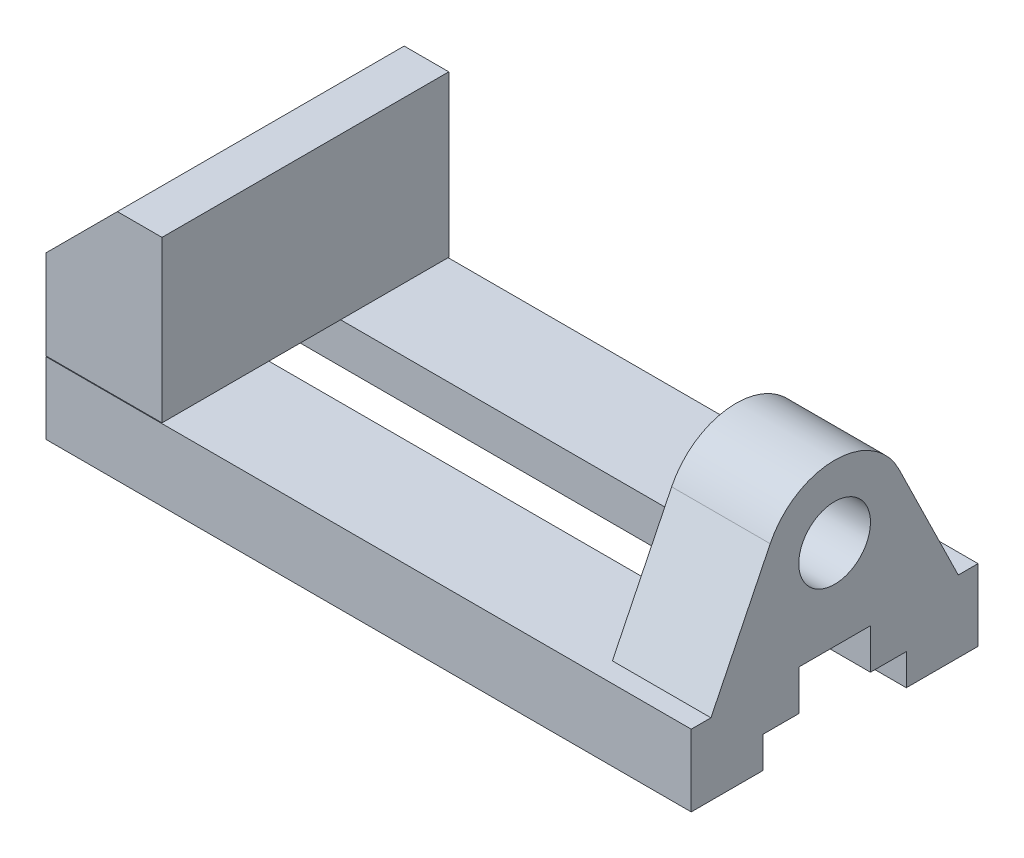
SolidWorks part; units mm, degrees
ref_plane "Front Plane" through (0, 0, 0) normal (0, 0, 1) x (1, 0, 0)
ref_plane "Top Plane" through (0, 0, 0) normal (0, 1, 0) x (1, 0, 0)
ref_plane "Right Plane" through (0, 0, 0) normal (1, 0, 0) x (0, 0, -1)
sketch "Sketch1" plane through (0, 0, 0) normal (0, 0, 1) x (1, 0, 0)
  line L1 (72, 8) -> (-72, 8)
  line L2 (72, 8) -> (72, -8)
  line L3 (72, -8) -> (-72, -8)
  line L4 (-72, 8) -> (-72, -8)
  line L5 (72, 8) -> (-72, -8) construction
  line L6 (72, -8) -> (-72, 8) construction
  point P0 (0, 0)
  dimension "D1" = 16
  dimension "D2" = 144
extrude "Boss-Extrude1" add sketch "Sketch1" along normal mid plane 64
ref_plane "Plane1" through (0, 0, 32) normal (0, 0, 1) x (1, 0, 0)
sketch "Sketch2" plane through (0, 0, 32) normal (0, 0, 1) x (1, 0, 0)
  line L0 (-72, 8.15) -> (-46.1084, 8.15)
  line L1 (-72, -8) -> (72, -8) construction
  line L6 (-56.0667, 44) -> (-72, 28.0667)
  line L8 (-72, 8.15) -> (-72, 28.0667)
  line L9 (-56.0667, 44) -> (-46.1084, 44)
  line L10 (-46.1084, 8.15) -> (-46.1084, 44)
  point P1 (0, 0)
  point P2 (0, 0)
  point P3 (-71.3163, 28.7504)
  dimension "D1" = 9.9583
  dimension "D2" = 35.85
  dimension "D3" = 22.5331
  dimension "D4" = 46.1084
  dimension "D5" = 72
  dimension "D6" = 15.9333
  dimension "D7" = 16.15
  dimension "D8" = 44
  dimension "D9" = 45
extrude "Boss-Extrude2" add sketch "Sketch2" against normal blind 64
ref_plane "Plane2" through (72, 0, 0) normal (1, 0, 0) x (0, 0, -1)
sketch "Sketch3" plane through (72, 0, 0) normal (1, 0, 0) x (0, 0, -1)
  line L0 (-27.5969, 8) -> (-32, 8)
  line L1 (-32, -8) -> (32, -8) construction
  line L2 (-32, 8) -> (-27.5969, 8) construction
  line L3 (-32, 8) -> (-32, -8)
  line L4 (27.5969, 8) -> (32, 8)
  line L5 (-32, 8.8) -> (-32, -8.8) construction
  line L6 (-32, 8) -> (32, 8) construction
  line L7 (27.5969, 8) -> (14.3722, 35.0314)
  line L8 (32, 8) -> (32, -8)
  line L9 (-32, -8) -> (32, -8)
  line L15 (0, 28) -> (0, 12) construction
  line L16 (-32, 1012.6082) -> (-32, 8) construction
  line L18 (-27.5969, 8) -> (-14.3722, 35.0314)
  line L19 (0, 67.6242) -> (21098.9131, 45314.3894) construction
  circle A0 centre (0, 28) radius 8
  arc A1 (14.3722, 35.0314) -> (-14.3722, 35.0314) centre (0, 28) ccw
  point P14 (0, 8)
  point P19 (0, 8)
  point P21 (0, 0)
  point P35 (-32, -1)
  dimension "D1" = 36
  dimension "D2" = 32
  dimension "D3" = 16
  dimension "D4" = 27.5969
  dimension "D5" = 27.5969
  dimension "D6" = 8
extrude "Boss-Extrude3" add sketch "Sketch3" against normal blind 22
sketch "Sketch4" plane through (72, 0, 0) normal (1, 0, 0) x (0, 0, -1)
  line L0 (-32, 8) -> (32, 8) construction
  line L1 (-32, 8.8) -> (-32, -8.8) construction
  line L2 (-32, 8) -> (-27.5969, 8) construction
  line L3 (8, 8) -> (-8, 8)
  line L4 (32, -8) -> (-32, -8) construction
  line L5 (-32, -8) -> (32, -8) construction
  line L6 (-16, -8) -> (16, -8)
  line L7 (-16, -8) -> (-16, -1)
  line L8 (-8, 8) -> (-8, -4.0342) construction
  line L9 (-16, -1) -> (-8, -1)
  line L10 (-8, -1) -> (-8, 8)
  line L11 (0, 8) -> (0, -10.9351) construction
  line L12 (8, -1) -> (8, 8)
  line L13 (16, -8) -> (16, -1)
  line L14 (16, -1) -> (8, -1)
  point P10 (0, 8)
  point P15 (0, -8)
  point P18 (0, -8)
  dimension "D1" = 16
  dimension "D2" = 32
  dimension "D3" = 7
extrude "Cut-Extrude1" cut sketch "Sketch4" against normal through all
